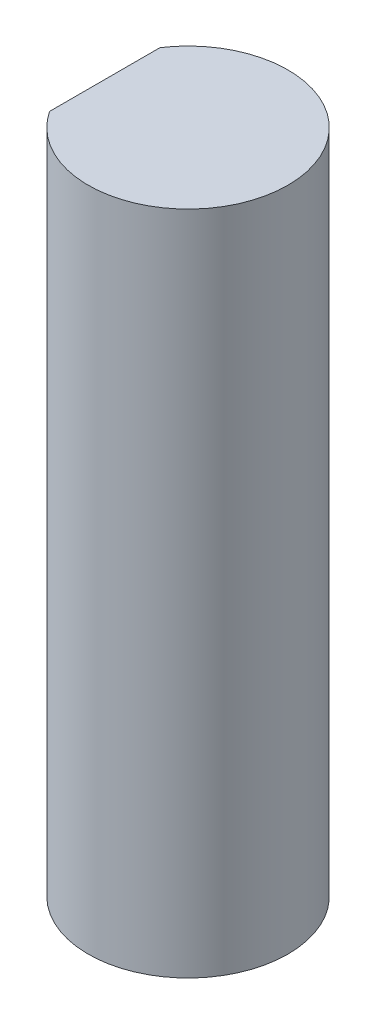
SolidWorks part; units mm, degrees
material "Alloy Steel"
ref_plane "Front Plane" through (0, 0, 0) normal (0, 0, 1) x (1, 0, 0)
ref_plane "Top Plane" through (0, 0, 0) normal (0, 1, 0) x (1, 0, 0)
ref_plane "Right Plane" through (0, 0, 0) normal (1, 0, 0) x (0, 0, -1)
sketch "Sketch1" plane through (0, 0, 0) normal (0, 1, 0) x (1, 0, 0)
  line L0 (-2.5, 1.6583) -> (-2.5, -1.6583)
  arc A0 (-2.5, -1.6583) -> (-2.5, 1.6583) centre (0, 0) ccw
  point P1 (3, 0)
  dimension "D1" = 6
  dimension "D2" = 5.5
extrude "Boss-Extrude1" add sketch "Sketch1" along normal blind 20
